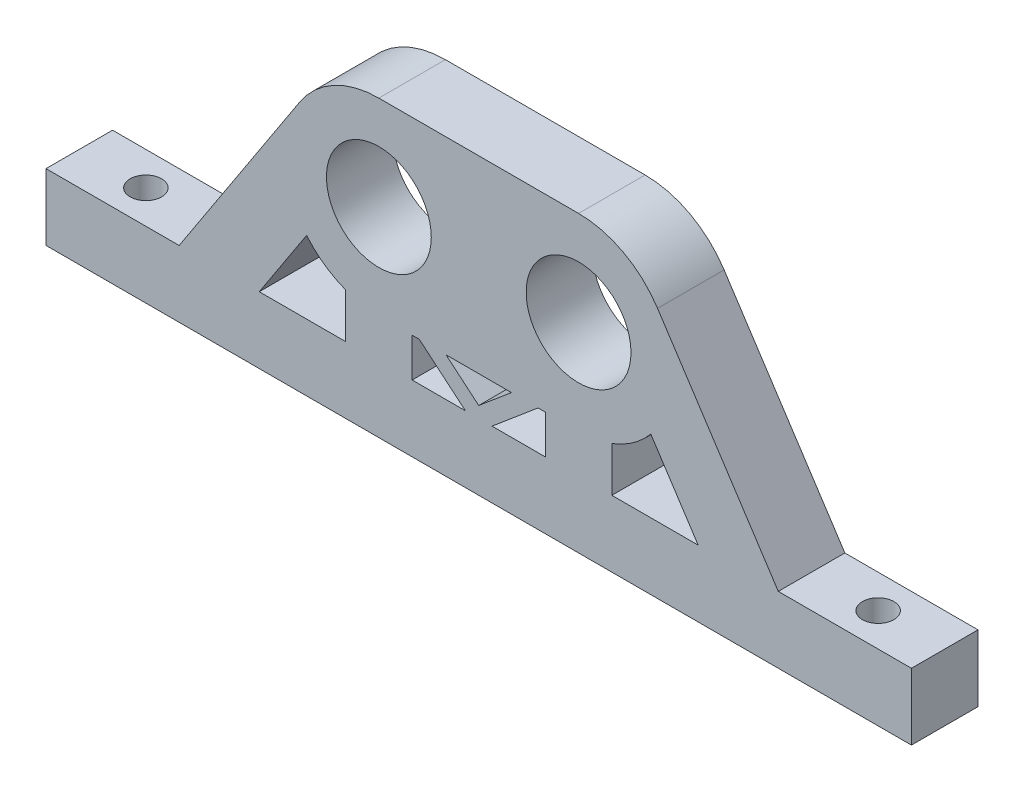
SolidWorks part; units mm, degrees
material "Pine"
ref_plane "Front Plane" through (0, 0, 0) normal (0, 0, 1) x (1, 0, 0)
ref_plane "Top Plane" through (0, 0, 0) normal (0, 1, 0) x (1, 0, 0)
ref_plane "Right Plane" through (0, 0, 0) normal (1, 0, 0) x (0, 0, -1)
sketch "Sketch1" plane through (0, 0, 0) normal (0, 0, 1) x (1, 0, 0)
  line L0 (0, 9) -> (19.05, 9)
  line L1 (0, -9) -> (19.05, -9)
  line L2 (-7.5341, 4.9232) -> (-19.05, -12.7)
  line L3 (-31.75, -19.05) -> (50.8, -19.05)
  line L4 (-31.75, -19.05) -> (-31.75, -12.7)
  line L5 (-31.75, -12.7) -> (50.8, -12.7)
  line L6 (50.8, -19.05) -> (50.8, -12.7)
  line L7 (-6.8917, -5.7883) -> (-11.4081, -12.7)
  line L8 (-3.175, -8.4214) -> (-3.175, -12.7)
  line L9 (3.175, -8.4214) -> (3.175, -12.7)
  line L10 (4.7745, -7.6292) -> (10.795, -12.7)
  line L11 (3.175, -8.4214) -> (8.255, -12.7)
  line L12 (9.525, -12.7) -> (9.525, 0) construction
  line L13 (14.2755, -7.6292) -> (8.255, -12.7)
  line L14 (15.875, -8.4214) -> (10.795, -12.7)
  line L15 (15.875, -8.4214) -> (15.875, -12.7)
  line L16 (22.225, -8.4214) -> (22.225, -12.7)
  line L17 (25.9417, -5.7883) -> (30.4581, -12.7)
  line L18 (26.5841, 4.9232) -> (38.1, -12.7)
  circle A0 centre (0, 0) radius 9
  circle A1 centre (19.05, 0) radius 9
  point P20 (0, 0)
  point P23 (9.525, -12.7)
  dimension "D1" = 18
  dimension "D2" = 18
  dimension "D3" = 19.05
  dimension "D4" = 6.35
  dimension "D7" = 12.7
  dimension "D8" = 3.175
  dimension "D9" = 3.175
  dimension "D10" = 6.3971
  dimension "D11" = 12.7
  dimension "D5" = 31.75
  dimension "D6" = 31.75
  dimension "D12" = 1.27
extrude "Boss-Extrude1" add sketch "Sketch1" against normal blind 6.35
sketch "Sketch2" plane through (0, 0, 0) normal (0, 0, 1) x (1, 0, 0)
  circle A0 centre (0, 0) radius 5
  circle A1 centre (19.05, 0) radius 5
  point P5 (0, 0)
  point P6 (0, 0)
  point P7 (0, 0)
  point P8 (0, 0)
  dimension "D3" = 19.05
  dimension "D1" = 10
  dimension "D2" = 10
extrude "Cut-Extrude1" cut sketch "Sketch2" against normal through all
sketch "Sketch3" plane through (0, -12.7, 0) normal (0, 1, 0) x (1, 0, 0)
  line L0 (-25.4, 0) -> (-25.4, 6.35) construction
  line L1 (-31.75, 6.35) -> (-19.05, 6.35) construction
  line L2 (44.45, 0) -> (44.45, 6.35) construction
  line L3 (38.1, 0) -> (50.8, 0) construction
  line L4 (38.1, 6.35) -> (50.8, 6.35) construction
  line L5 (-31.75, 0) -> (-19.05, 0) construction
  circle A0 centre (44.45, 3.175) radius 1.5
  circle A1 centre (-25.4, 3.175) radius 1.5
  point P14 (0, 0)
  point P17 (0, 0)
  point P18 (0, 0)
  dimension "D1" = 3
  dimension "D2" = 3
extrude "Cut-Extrude2" cut sketch "Sketch3" against normal through all
equation "\"D2@Sketch1\"=\"D1@Sketch1\""
equation "\"D9@Sketch1\"=\"D8@Sketch1\""
equation "\"D6@Sketch1\"=\"D5@Sketch1\""
equation "\"D2@Sketch2\"=\"D1@Sketch2\""
equation "\"D2@Sketch3\"=\"D1@Sketch3\""
